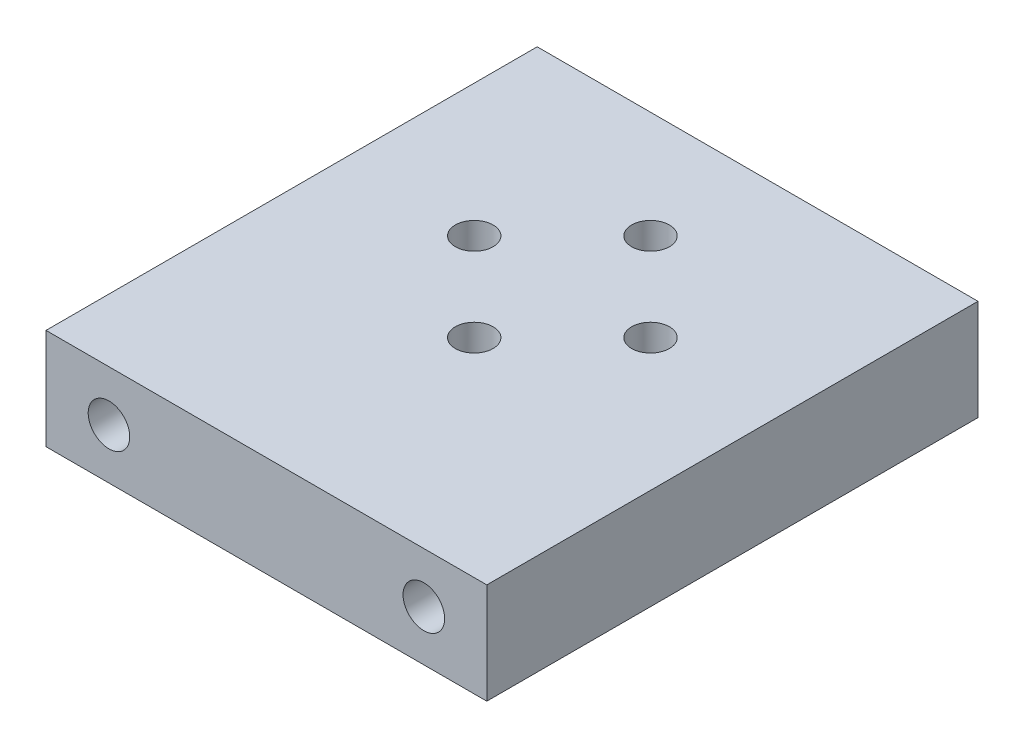
SolidWorks part; units mm, degrees
ref_plane "前视基准面" through (0, 0, 0) normal (0, 0, 1) x (1, 0, 0)
ref_plane "上视基准面" through (0, 0, 0) normal (0, 1, 0) x (1, 0, 0)
ref_plane "右视基准面" through (0, 0, 0) normal (1, 0, 0) x (0, 0, -1)
sketch "草图1" plane through (0, 0, 0) normal (0, 1, 0) x (1, 0, 0)
  line L1 (-17.5, 19.5) -> (17.5, 19.5)
  line L2 (-17.5, 19.5) -> (-17.5, -19.5)
  line L3 (-17.5, -19.5) -> (17.5, -19.5)
  line L4 (17.5, 19.5) -> (17.5, -19.5)
  line L5 (0, -19.5) -> (0, 19.5) construction
  line L6 (-17.5, 0) -> (17.5, 0) construction
  point P0 (0, 0)
  dimension "D1" = 35
  dimension "D2" = 39
extrude "凸台-拉伸1" add sketch "草图1" along normal blind 8
sketch "草图2" plane through (0, 0, -19.5) normal (0, 0, -1) x (-1, 0, 0)
  line L0 (-17.5, 4) -> (17.5, 4) construction
  line L1 (-17.5, 8) -> (-17.5, 0) construction
  line L2 (17.5, 8) -> (17.5, 0) construction
  line L3 (0, 8) -> (0, 0) construction
  line L4 (-17.5, 8) -> (17.5, 8) construction
  circle A0 centre (12.5, 4) radius 1.65
  circle A1 centre (-12.5, 4) radius 1.65
  point P6 (12.5, 4)
  point P12 (-12.5, 4)
  dimension "D1" = 3.3
  dimension "D2" = 25
extrude "切除-拉伸1" cut sketch "草图2" against normal blind 12
sketch "草图5" plane through (0, 0, 0) normal (0, 1, 0) x (1, 0, 0)
  line L0 (-17.5, -19.5) -> (17.5, -19.5) construction
  circle A0 centre (0, 4) radius 5.5
  point P3 (0, 0)
  dimension "D1" = 11
  dimension "D2" = 23.5
extrude "切除-拉伸3" cut sketch "草图5" along normal blind 5
sketch "草图7" plane through (0, 0, 0) normal (0, -1, 0) x (1, 0, 0)
  line L0 (0, 19.5) -> (0, -19.5) construction
  line L1 (-17.5, 19.5) -> (17.5, 19.5) construction
  line L2 (17.5, -19.5) -> (-17.5, -19.5) construction
  line L3 (1.5, -11) -> (1.5, -9)
  line L4 (1.5, -9) -> (-1.5, -9)
  line L5 (-1.5, -11) -> (-1.5, -9)
  line L6 (-7, -5.5) -> (-5, -5.5)
  line L7 (-5, -5.5) -> (-5, -2.5)
  line L8 (-7, -2.5) -> (-5, -2.5)
  line L9 (-1.5, 3) -> (-1.5, 1)
  line L10 (-1.5, 1) -> (1.5, 1)
  line L11 (1.5, 3) -> (1.5, 1)
  line L12 (7, -2.5) -> (5, -2.5)
  line L13 (5, -2.5) -> (5, -5.5)
  line L14 (7, -5.5) -> (5, -5.5)
  circle A0 centre (0, -4) radius 7 construction
  arc A1 (-1.5, -11) -> (1.5, -11) centre (0, -11) ccw
  arc A2 (1.4914, -10.8393) -> (0, -9.5) centre (0, -11) ccw construction
  arc A3 (0, -9.5) -> (-1.4914, -10.8393) centre (0, -11) ccw construction
  arc A4 (1.5, -11) -> (1.4914, -10.8393) centre (0, -11) ccw construction
  arc A5 (-1.4914, -10.8393) -> (-1.5, -11) centre (0, -11) ccw construction
  arc A6 (-7, -2.5) -> (-7, -5.5) centre (-7, -4) ccw
  arc A7 (-6.8393, -5.4914) -> (-5.5, -4) centre (-7, -4) ccw construction
  arc A8 (-5.5, -4) -> (-6.8393, -2.5086) centre (-7, -4) ccw construction
  arc A9 (-7, -5.5) -> (-6.8393, -5.4914) centre (-7, -4) ccw construction
  arc A10 (-6.8393, -2.5086) -> (-7, -2.5) centre (-7, -4) ccw construction
  arc A11 (1.5, 3) -> (-1.5, 3) centre (0, 3) ccw
  arc A12 (-1.4914, 2.8393) -> (0, 1.5) centre (0, 3) ccw construction
  arc A13 (0, 1.5) -> (1.4914, 2.8393) centre (0, 3) ccw construction
  arc A14 (-1.5, 3) -> (-1.4914, 2.8393) centre (0, 3) ccw construction
  arc A15 (1.4914, 2.8393) -> (1.5, 3) centre (0, 3) ccw construction
  arc A16 (7, -5.5) -> (7, -2.5) centre (7, -4) ccw
  arc A17 (6.8393, -2.5086) -> (5.5, -4) centre (7, -4) ccw construction
  arc A18 (5.5, -4) -> (6.8393, -5.4914) centre (7, -4) ccw construction
  arc A19 (7, -2.5) -> (6.8393, -2.5086) centre (7, -4) ccw construction
  arc A20 (6.8393, -5.4914) -> (7, -5.5) centre (7, -4) ccw construction
  dimension "D1" = 14
  dimension "D2" = 3
  dimension "D3" = 2
  dimension "D4" = 4
extrude "切除-拉伸5" cut sketch "草图7" against normal blind 5
sketch "草图8" plane through (0, 5, 0) normal (0, -1, 0) x (1, 0, 0)
  line L0 (0, -12.5) -> (0, 4.5) construction
  line L1 (8.5, -4) -> (-8.5, -4) construction
  circle A0 centre (0, -11) radius 1.5
  arc A2 (7, -5.5) -> (7, -2.5) centre (7, -4) ccw construction
  arc A3 (-7, -2.5) -> (-7, -5.5) centre (-7, -4) ccw construction
  arc A4 (1.5, 3) -> (-1.5, 3) centre (0, 3) ccw construction
  circle A5 centre (7, -4) radius 1.5
  circle A6 centre (0, 3) radius 1.5
  circle A7 centre (-7, -4) radius 1.5
  point P16 (0, -4)
  dimension "D1" = 3
extrude "切除-拉伸6" cut sketch "草图8" against normal blind 5
sketch "草图9" plane through (0, 0, 19.5) normal (0, 0, 1) x (1, 0, 0)
  line L0 (-17.5, 4) -> (17.5, 4) construction
  line L1 (-17.5, 8) -> (-17.5, 0) construction
  line L2 (17.5, 8) -> (17.5, 0) construction
  line L3 (0, 8) -> (0, 0) construction
  line L4 (-17.5, 8) -> (17.5, 8) construction
  circle A0 centre (-12.5, 4) radius 1.65
  circle A1 centre (12.5, 4) radius 1.65
  dimension "D1" = 3.3
  dimension "D2" = 12.5
extrude "切除-拉伸7" cut sketch "草图9" against normal blind 12
